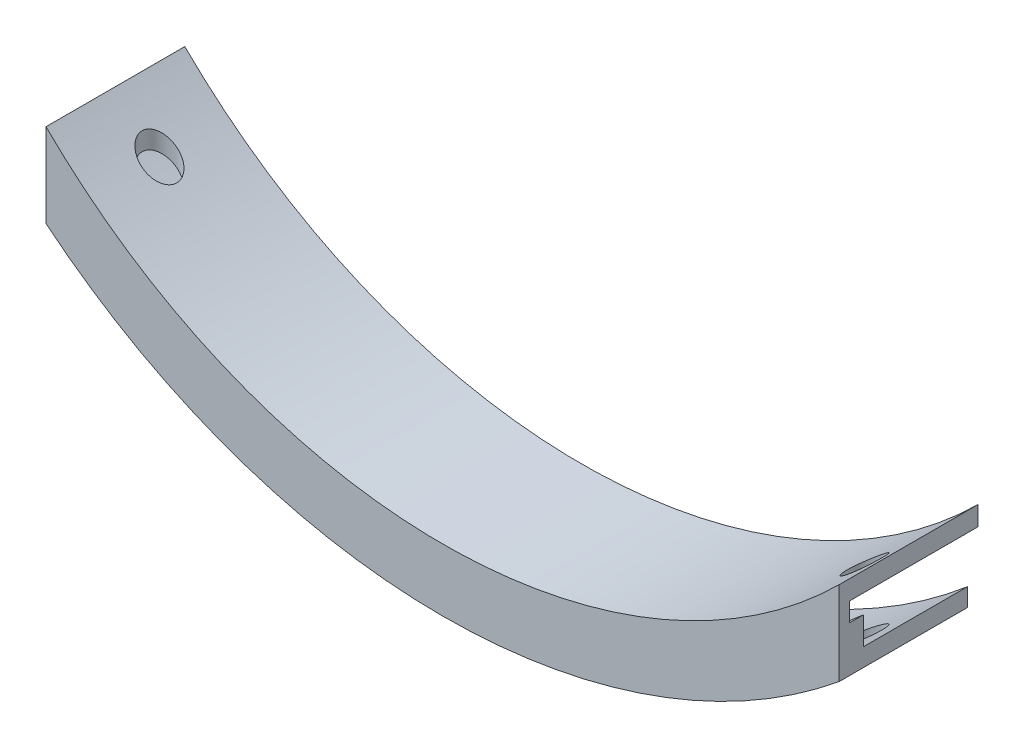
SolidWorks part; units mm, degrees
ref_plane "Front Plane" through (0, 0, 0) normal (0, 0, 1) x (1, 0, 0)
ref_plane "Top Plane" through (0, 0, 0) normal (0, 1, 0) x (1, 0, 0)
ref_plane "Right Plane" through (0, 0, 0) normal (1, 0, 0) x (0, 0, -1)
sketch "Sketch1" plane through (0, 0, 0) normal (0, 0, 1) x (1, 0, 0)
  line L1 (0, 0) -> (228.6, 0)
  line L2 (0, 0) -> (0, 70)
  line L3 (0, 70) -> (228.6, 70) construction
  line L4 (228.6, 0) -> (228.6, 70)
  arc A1 (0, 70) -> (228.6, 70) centre (114.3, 185.5065) ccw
  dimension "D1" = 228.6
  dimension "D3" = 162.5
  dimension "D2" = 70
extrude "Boss-Extrude1" add sketch "Sketch1" along normal blind 40
ref_point "Point1"
ref_plane "Plane4" through (114.3, 0, 0) normal (1, 0, 0) x (0, 0, -1)
sketch "Sketch2" plane through (114.3, 0, 0) normal (1, 0, 0) x (0, 0, -1)
  line L0 (-40, 70) -> (0, 70) construction
  line L1 (-33, 15.0065) -> (-7, 15.0065)
  line L2 (-33, 15.0065) -> (-33, 9.0065)
  line L3 (-33, 9.0065) -> (-7, 9.0065)
  line L4 (-7, 15.0065) -> (-7, 9.0065)
  line L6 (-40, 23.0065) -> (0, 23.0065) construction
  line L7 (-40, 23.0065) -> (0, 23.0065) construction
  point P6 (-20, 70)
  point P7 (-20, 15.0065)
  dimension "D1" = 6
  dimension "D2" = 26
  dimension "D3" = 8
ref_axis "Axis1" through (114.3, 185.5065, 40) along (0, 0, 1)
revolve "Cut-Revolve1" cut sketch "Sketch2" angle 360 about axis through (114.3, 185.5065, 40) along (0, 0, 1)
sketch "Sketch4" plane through (0, 0, 0) normal (0, -1, 0) x (1, 0, 0)
  line L0 (0, 20) -> (228.6, 20) construction
  line L1 (0, 40) -> (0, 0) construction
  line L2 (228.6, 40) -> (228.6, 0) construction
  line L3 (114.3, 80.0645) -> (114.3, -38.0645) construction
  line L4 (12.7, 20) -> (215.9, 20) construction
  circle A2 centre (12.7, 20) radius 2.5
  circle A3 centre (215.9, 20) radius 2.5
  point P9 (114.3, 20)
  point P13 (114.3, 20)
  dimension "D1" = 203.2
  dimension "D2" = 5
  dimension "D3" = 5
extrude "Cut-Extrude1" cut sketch "Sketch4" against normal through all both and the other way through all
ref_plane "Plane5" through (0, 70, 0) normal (0, -1, 0) x (-1, 0, 0)
sketch "Sketch7" plane through (0, 70, 0) normal (0, -1, 0) x (-1, 0, 0)
  circle A0 centre (-215.9, -20) radius 5
  circle A1 centre (-12.7, -20) radius 5
  dimension "D1" = 10
  dimension "D2" = 10
extrude "Cut-Extrude3" cut sketch "Sketch7" along normal offset from surface (62 mm away) 8 up to face at (215.9, 0, 22.5)
sketch "Sketch8" plane through (114.3, 0, 0) normal (1, 0, 0) x (0, 0, -1)
  line L0 (-40, 0) -> (0, 0) construction
  line L1 (-40, 23.0065) -> (0, 23.0065) construction
  line L2 (-40, 0) -> (0, 0) construction
  line L3 (-40, 23.0065) -> (0, 23.0065) construction
  line L4 (-40, 23.0065) -> (-40, 0) construction
  line L5 (0, 23.0065) -> (0, 0) construction
  line L6 (-7, 15.0065) -> (-37, 15.0065)
  line L7 (-37, 15.0065) -> (-37, 19.0065)
  line L8 (-37, 19.0065) -> (0, 19.0065)
  line L12 (-40, 5.0065) -> (-3, 5.0065)
  line L14 (-33, 9.0065) -> (-7, 9.0065) construction
  line L15 (-33, 15.0065) -> (-7, 15.0065) construction
  line L16 (-7, 51.0158) -> (-7, 9.0065) construction
  line L17 (-7, 15.0065) -> (-7, 9.0065)
  line L18 (-7, 9.0065) -> (-3, 9.0065)
  line L19 (-3, 9.0065) -> (-3, 5.0065)
  line L20 (-33, 9.0065) -> (-33, 51.0158) construction
  line L21 (0, 19.0065) -> (0, -48.7775)
  line L22 (0, -48.7775) -> (-40, -48.7775)
  line L23 (-40, -48.7775) -> (-40, 5.0065)
  dimension "D1" = 4
  dimension "D2" = 4
  dimension "D3" = 4
  dimension "D4" = 4
revolve "Cut-Revolve4" cut sketch "Sketch8" angle 360 about axis through (114.3, 185.5065, 40) along (0, 0, 1)
